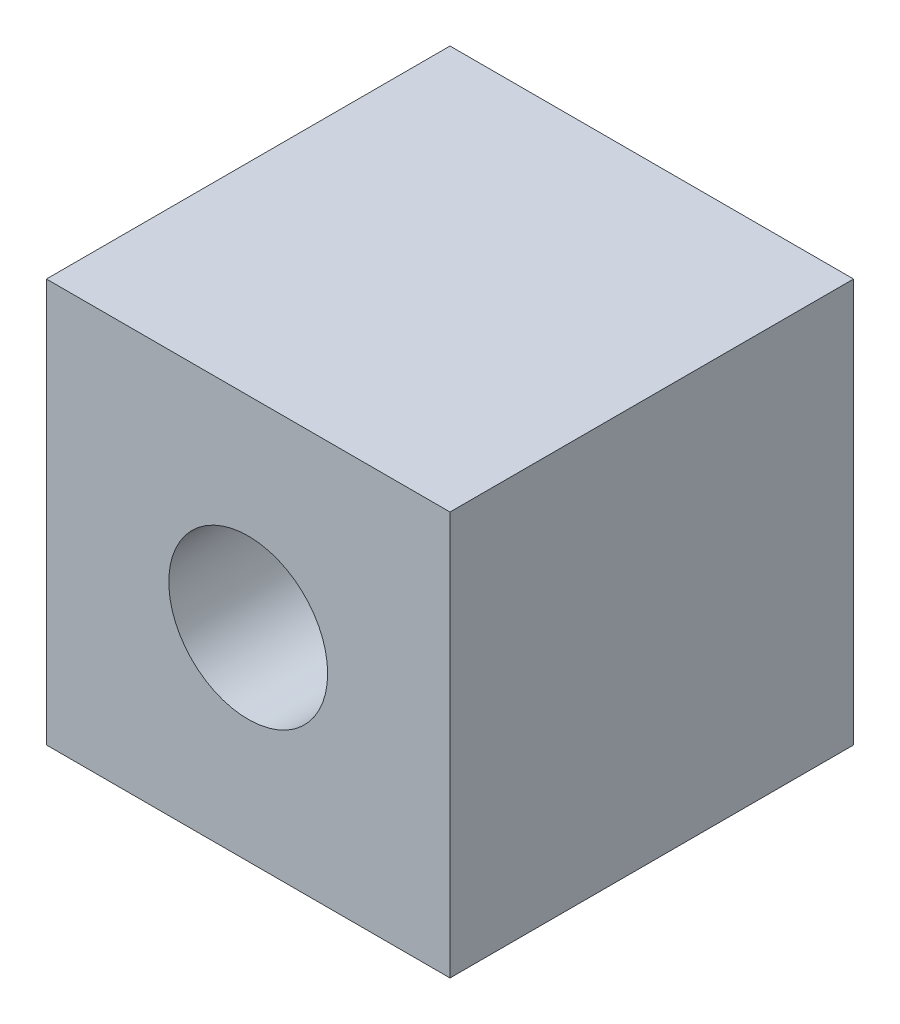
SolidWorks part; units mm, degrees
ref_plane "Front Plane" through (0, 0, 0) normal (0, 0, 1) x (1, 0, 0)
ref_plane "Top Plane" through (0, 0, 0) normal (0, 1, 0) x (1, 0, 0)
ref_plane "Right Plane" through (0, 0, 0) normal (1, 0, 0) x (0, 0, -1)
sketch "Sketch2" plane through (0, 0, 0) normal (0, 1, 0) x (1, 0, 0)
  line L1 (-6.35, -6.35) -> (6.35, -6.35)
  line L2 (-6.35, -6.35) -> (-6.35, 6.35)
  line L3 (-6.35, 6.35) -> (6.35, 6.35)
  line L4 (6.35, -6.35) -> (6.35, 6.35)
  line L5 (-6.35, -6.35) -> (6.35, 6.35) construction
  line L6 (-6.35, 6.35) -> (6.35, -6.35) construction
  point P1 (0, 0)
  dimension "D1" = 12.7
  dimension "D2" = 12.7
extrude "Boss-Extrude1" add sketch "Sketch2" along normal blind 12.7
sketch "Sketch3" plane through (0, 0, 6.35) normal (0, 0, 1) x (1, 0, 0)
  line L0 (-6.35, 0) -> (0, 0)
  line L1 (0, 0) -> (0, 6.3735)
  circle A0 centre (0, 6.3735) radius 2.5
  dimension "D1" = 5
extrude "Cut-Extrude1" cut sketch "Sketch3" against normal blind 6.35
